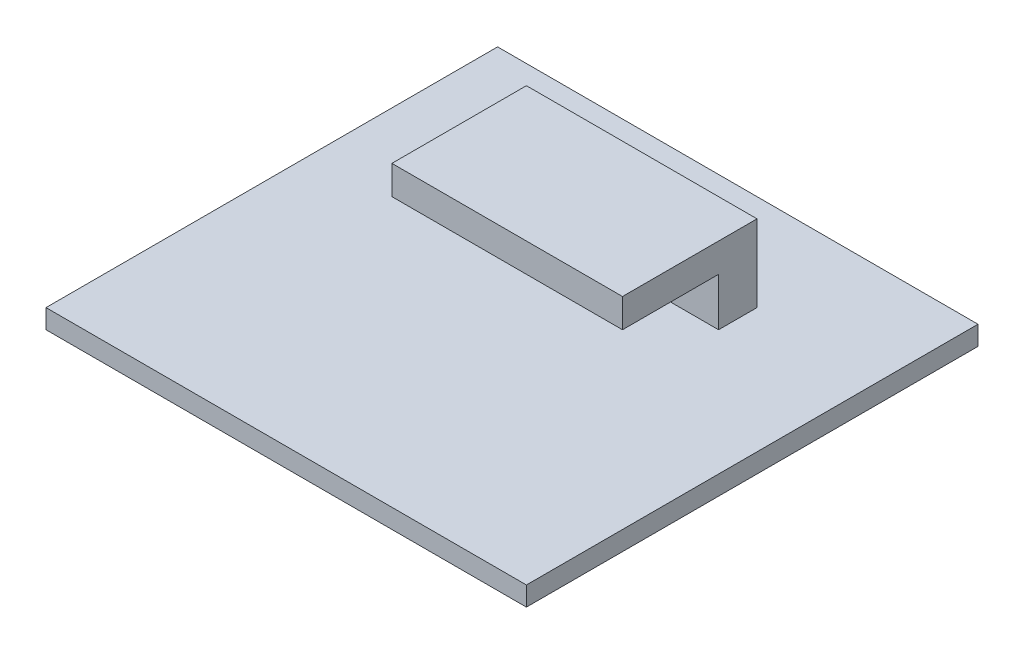
SolidWorks part; units mm, degrees
ref_plane "Спереди" through (0, 0, 0) normal (0, 0, 1) x (1, 0, 0)
ref_plane "Сверху" through (0, 0, 0) normal (0, 1, 0) x (1, 0, 0)
ref_plane "Справа" through (0, 0, 0) normal (1, 0, 0) x (0, 0, -1)
sketch "Эскиз1" plane through (0, 0, 0) normal (0, 1, 0) x (1, 0, 0)
  line L1 (0, 0) -> (50, 0)
  line L2 (0, 0) -> (0, 47)
  line L3 (0, 47) -> (50, 47)
  line L4 (50, 0) -> (50, 47)
extrude "Бобышка-Вытянуть1" add sketch "Эскиз1" along normal blind 2
sketch "Эскиз2" plane through (0, 2, 0) normal (0, 1, 0) x (1, 0, 0)
  line L2 (25, 37) -> (13, 37)
  line L3 (13, 37) -> (13, 33)
  line L4 (13, 33) -> (37, 33)
  line L5 (37, 33) -> (37, 37)
  line L6 (37, 37) -> (25, 37)
extrude "Бобышка-Вытянуть2" add sketch "Эскиз2" along normal blind 8
sketch "Эскиз3" plane through (0, 0, -33) normal (0, 0, 1) x (1, 0, 0)
  line L0 (37, 10) -> (37, 2) construction
  line L1 (13, 10) -> (37, 10)
  line L2 (13, 10) -> (13, 7)
  line L3 (13, 7) -> (37, 7)
  line L4 (37, 10) -> (37, 7)
extrude "Бобышка-Вытянуть3" add sketch "Эскиз3" along normal blind 10
